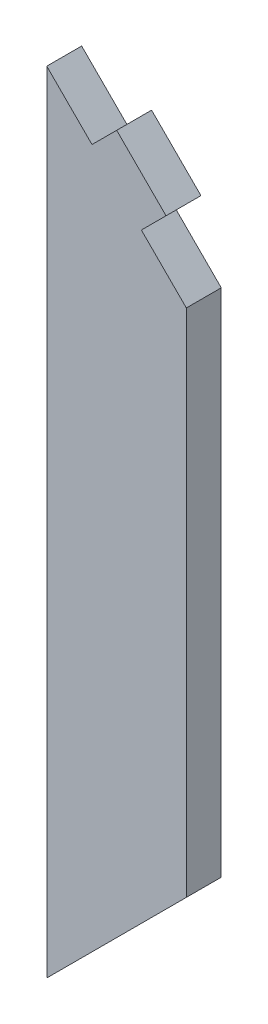
SolidWorks part; units mm, degrees
material "Pin"
ref_plane "Front" through (0, 0, 0) normal (0, 0, 1) x (1, 0, 0)
ref_plane "Top" through (0, 0, 0) normal (0, 1, 0) x (1, 0, 0)
ref_plane "Right" through (0, 0, 0) normal (1, 0, 0) x (0, 0, -1)
sketch "Esquisse1" plane through (0, 0, 0) normal (0, 0, 1) x (1, 0, 0)
  line L0 (-12.7, -71.8426) -> (12.7, -46.4426)
  line L2 (-12.7, 71.8426) -> (-12.7, -71.8426)
  line L4 (12.7, 46.4426) -> (12.7, -46.4426)
  line L5 (-12.7, 71.8426) -> (12.7, -71.8426) construction
  line L6 (-12.7, -71.8426) -> (12.7, 71.8426) construction
  line L7 (-12.7, 71.8426) -> (12.7, 46.4426)
  point P0 (0, 0)
  dimension "D1" = 25.4
  dimension "D2" = 143.6853
  dimension "D3" = 25.4
  dimension "D4" = 45
  dimension "D5" = 45
extrude "Boss.-Extru.1" add sketch "Esquisse1" along normal blind 6.35
sketch "Esquisse2" plane through (29.5713, 29.5713, 0) normal (0.7071, 0.7071, 0) x (0, 0, -1)
  line L0 (-6.35, 23.8596) -> (-6.35, 59.7807) construction
  line L1 (-6.35, 48.1344) -> (0, 48.1344)
  line L2 (-6.35, 48.1344) -> (-6.35, 35.4344)
  line L3 (-6.35, 35.4344) -> (0, 35.4344)
  line L4 (0, 48.1344) -> (0, 35.4344)
  line L5 (0, 23.8596) -> (0, 59.7807) construction
  line L6 (-6.35, 23.8596) -> (0, 23.8596) construction
  point P8 (-6.35, 41.7844)
  dimension "D1" = 12.7
  dimension "D2" = 17.9248
extrude "Boss.-Extru.2" add sketch "Esquisse2" along normal blind 6.35
